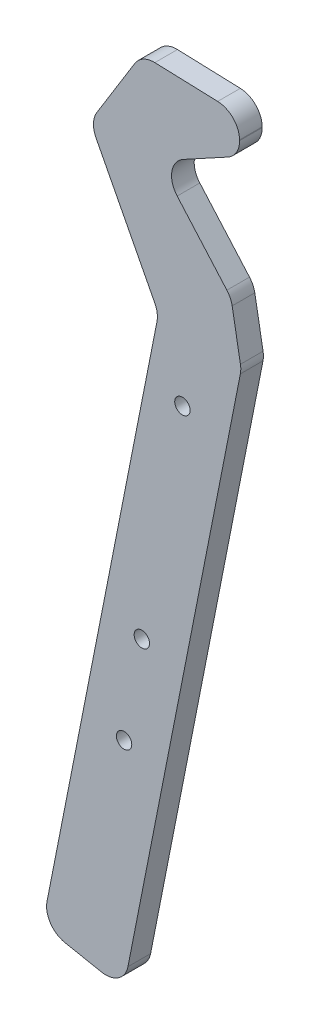
SolidWorks part; units mm, degrees
ref_plane "Front Plane" through (0, 0, 0) normal (0, 0, 1) x (1, 0, 0)
ref_plane "Top Plane" through (0, 0, 0) normal (0, 1, 0) x (1, 0, 0)
ref_plane "Right Plane" through (0, 0, 0) normal (1, 0, 0) x (0, 0, -1)
sketch "Sketch1" plane through (0, 0, 0) normal (0, 0, 1) x (1, 0, 0)
  line L0 (-6.0705, 24.8122) -> (-19.9581, 25.2883)
  line L1 (-24.3841, 22.9175) -> (-32.7677, 9.3354)
  line L2 (-32.954, 4.412) -> (-19.9448, -20.7391)
  line L3 (-19.4805, -24.0044) -> (-43.7719, -147.0807)
  line L4 (-39.8347, -152.9542) -> (-31.7663, -154.5467)
  line L5 (-25.8928, -150.6094) -> (-1.0625, -24.8027)
  line L6 (-1.046, -22.9542) -> (-2.8794, -12.7032)
  line L7 (-4.0426, -10.2862) -> (-15.0242, 2.2321)
  line L8 (-13.6609, 9.9182) -> (-3.8449, 15.2758)
  line L9 (-1.2406, 19.7127) -> (-1.242, 19.8632)
  line L10 (-26.7485, -107.7297) -> (-13.8654, -37.3574) construction
  circle A0 centre (-13.8654, -37.3574) radius 1.7
  arc A1 (-43.7719, -147.0807) -> (-39.8347, -152.9542) centre (-38.8665, -148.0488) ccw
  circle A2 centre (-26.7485, -107.7297) radius 1.7
  arc A3 (-31.7663, -154.5467) -> (-25.8928, -150.6094) centre (-30.7982, -149.6413) ccw
  arc A4 (-19.9448, -20.7391) -> (-19.4805, -24.0044) centre (-24.3859, -23.0362) cw
  arc A5 (-1.0625, -24.8027) -> (-1.046, -22.9542) centre (-5.9679, -23.8345) ccw
  arc A6 (-32.7677, 9.3354) -> (-32.954, 4.412) centre (-28.5129, 6.7092) ccw
  arc A7 (-2.8794, -12.7032) -> (-4.0426, -10.2862) centre (-7.8013, -13.5835) ccw
  arc A8 (-15.0242, 2.2321) -> (-13.6609, 9.9182) centre (-11.2655, 5.5294) cw
  arc A9 (-3.8449, 15.2758) -> (-1.2406, 19.7127) centre (-6.2403, 19.6647) ccw
  arc A10 (-6.0705, 24.8122) -> (-1.242, 19.8632) centre (-6.2418, 19.8152) cw
  arc A11 (-19.9581, 25.2883) -> (-24.3841, 22.9175) centre (-20.1294, 20.2913) ccw
  circle A12 centre (-22.8256, -86.4126) radius 1.7
  dimension "D1" = 5
extrude "Boss-Extrude1" add sketch "Sketch1" along normal blind 5
